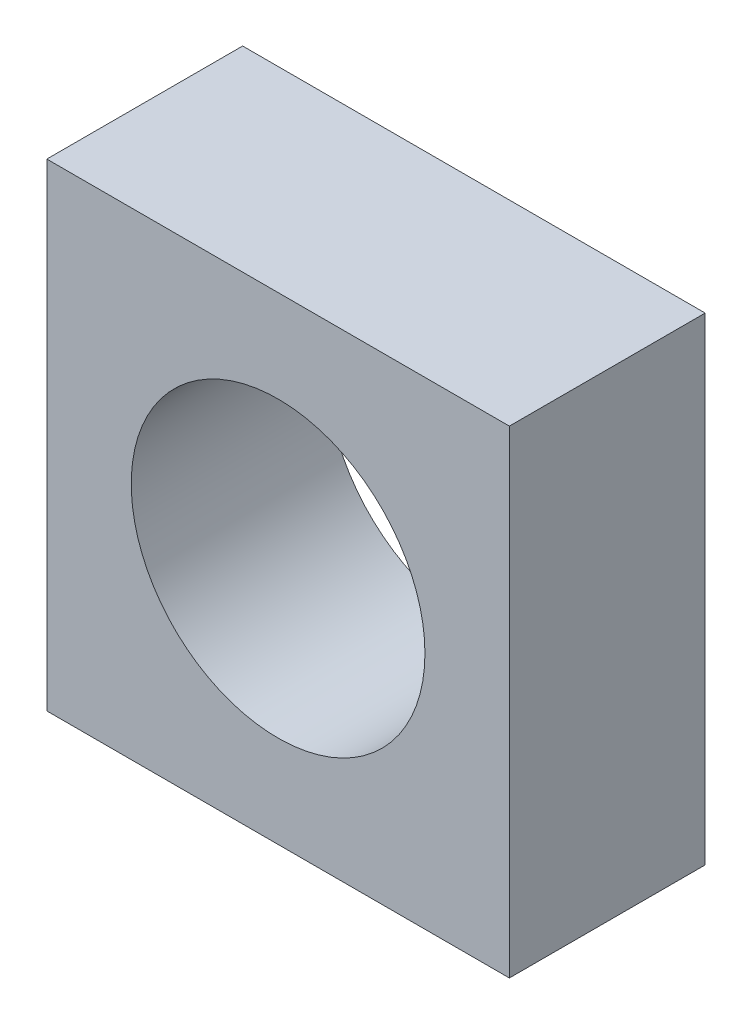
SolidWorks part; units mm, degrees
ref_plane "Alzado" through (0, 0, 0) normal (0, 0, 1) x (1, 0, 0)
ref_plane "Planta" through (0, 0, 0) normal (0, 1, 0) x (1, 0, 0)
ref_plane "Vista lateral" through (0, 0, 0) normal (1, 0, 0) x (0, 0, -1)
sketch "Croquis1" plane through (0, 0, 0) normal (0, 0, 1) x (1, 0, 0)
  line L1 (30, -31) -> (-30, -31)
  line L2 (30, -31) -> (30, 31)
  line L3 (30, 31) -> (-30, 31)
  line L4 (-30, -31) -> (-30, 31)
  line L5 (30, -31) -> (-30, 31) construction
  line L6 (30, 31) -> (-30, -31) construction
  circle A0 centre (0, 0) radius 19.05
  point P0 (0, 0)
  dimension "D3" = 38.1
  dimension "D1" = 62
  dimension "D2" = 60
extrude "Saliente-Extruir1" add sketch "Croquis1" along normal blind 25.4
